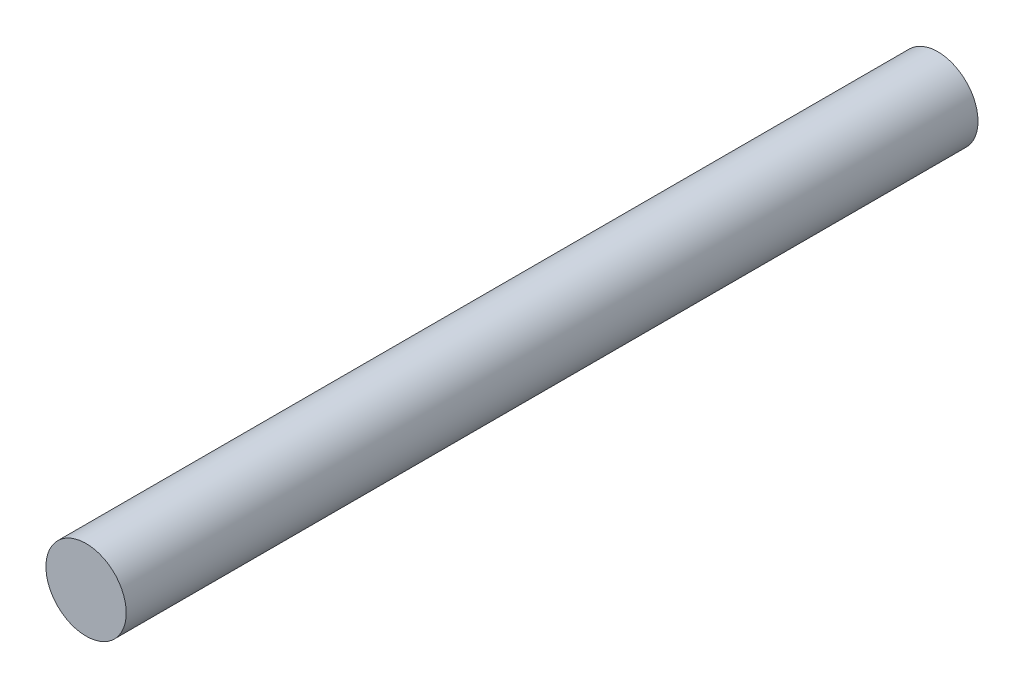
SolidWorks part; units mm, degrees
ref_plane "Front Plane" through (0, 0, 0) normal (0, 0, 1) x (1, 0, 0)
ref_plane "Top Plane" through (0, 0, 0) normal (0, 1, 0) x (1, 0, 0)
ref_plane "Right Plane" through (0, 0, 0) normal (1, 0, 0) x (0, 0, -1)
ref_plane "Plane1"
sketch "Sketch1" plane through (0, 0, 0) normal (0, 0, 1) x (1, 0, 0)
  circle A0 centre (0, 0) radius 1.65
  dimension "D1" = 3.3
extrude "Extrusion1" add sketch "Sketch1" along normal blind 35
